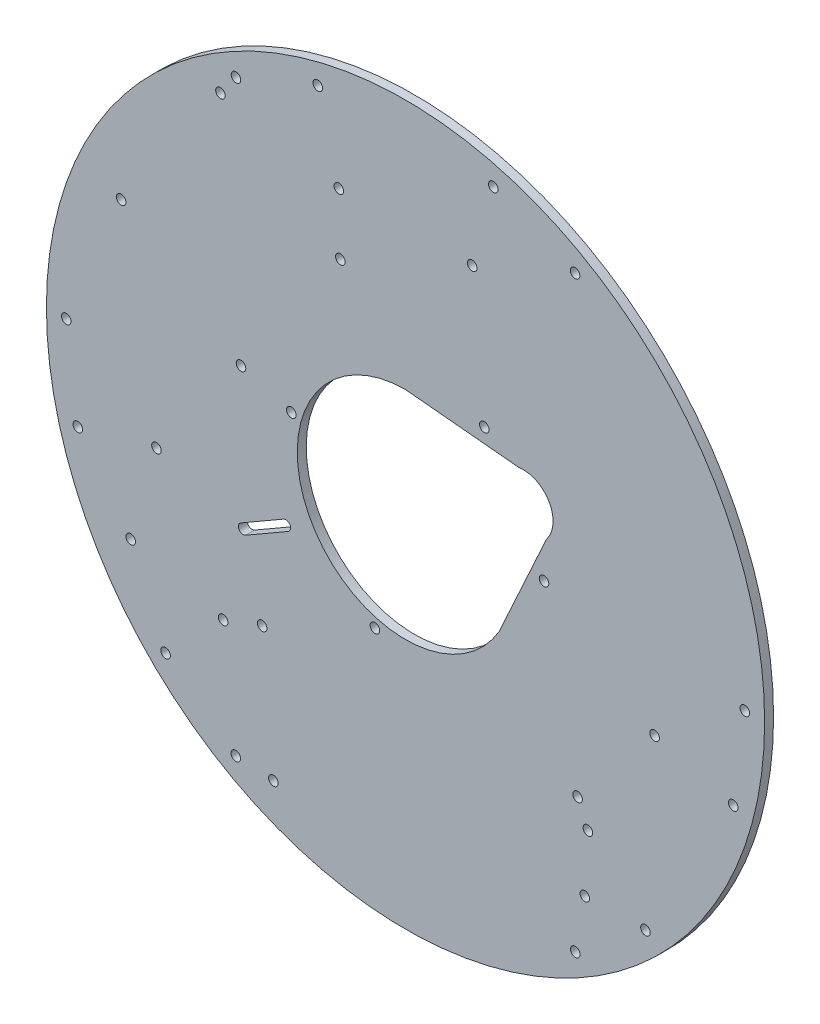
SolidWorks part; units mm, degrees
ref_plane "Front Plane" through (0, 0, 0) normal (0, 0, 1) x (1, 0, 0)
ref_plane "Top Plane" through (0, 0, 0) normal (0, 1, 0) x (1, 0, 0)
ref_plane "Right Plane" through (0, 0, 0) normal (1, 0, 0) x (0, 0, -1)
sketch "Sketch1" plane through (0, 0, 0) normal (0, 0, 1) x (1, 0, 0)
  line L0 (-65.1101, 48.691) -> (-135.9392, -73.9885)
  line L1 (-135.9392, -73.9885) -> (-113.0524, -113.6295)
  line L2 (-113.0524, -113.6295) -> (28.6057, -113.6295)
  line L3 (28.6057, -113.6295) -> (51.4924, -73.9885)
  line L4 (51.4924, -73.9885) -> (-19.3366, 48.691)
  line L5 (-19.3366, 48.691) -> (-65.1101, 48.691)
  line L9 (-42.2234, -10.309) -> (-2.8192, -14.059)
  line L10 (-10.83, -64.684) -> (5.6245, -28.684)
  circle A0 centre (-15.8503, -7.9885) radius 1.6
  circle A1 centre (4.1497, -42.6295) radius 1.6
  circle A2 centre (-80.4721, -36.0603) radius 1.6
  circle A3 centre (-52.4721, -84.5577) radius 1.6
  arc A4 (-42.2234, -10.309) -> (-10.83, -64.684) centre (-42.2234, -46.559) ccw
  arc A5 (5.6245, -28.684) -> (-2.8192, -14.059) centre (-2.8192, -23.809) ccw
extrude "Boss-Extrude1" add sketch "Sketch1" along normal blind 3
sketch "Sketch2" plane through (0, 0, 3) normal (0, 0, 1) x (1, 0, 0)
  circle A0 centre (-2.8192, -23.809) radius 10
extrude "Cut-Extrude1" cut sketch "Sketch2" against normal through all
sketch "Sketch3" plane through (0, 0, 3) normal (0, 0, 1) x (1, 0, 0)
  line L0 (-65.1101, 48.691) -> (-65.1101, 71.4883)
  circle A0 centre (-42.2234, -46.559) radius 120.2454
extrude "Boss-Extrude2" add sketch "Sketch3" against normal blind 3
sketch "Sketch4" plane through (0, 0, 0) normal (0, 0, -1) x (-1, 0, 0)
  line L0 (-5.841, -18.809) -> (73.6168, -64.684)
  line L1 (73.6168, -64.684) -> (146.359, -106.6817)
  line L2 (42.2234, -46.559) -> (31.7433, -166.3468)
  line L3 (42.2234, -46.559) -> (140.7227, 22.411)
  line L4 (35.8225, -119.7215) -> (93.082, -124.731)
  line L9 (93.082, -124.731) -> (95.2909, -99.4825)
  line L10 (95.2909, -99.4825) -> (-19.2715, -89.4596)
  line L11 (-19.2715, -89.4596) -> (-23.6894, -139.9567)
  line L12 (-23.6894, -139.9567) -> (90.873, -149.9796)
  line L13 (90.873, -149.9796) -> (93.082, -124.731)
  line L14 (-23.6894, -139.9567) -> (-18.9575, -140.3707)
  line L15 (-18.9575, -140.3707) -> (-17.8026, -127.1711)
  line L16 (90.873, -149.9796) -> (86.1411, -149.5656)
  line L17 (86.1411, -149.5656) -> (86.4679, -145.8299)
  line L18 (106.598, -1.4834) -> (129.5343, 14.5768)
  line L19 (129.5343, 14.5768) -> (153.7938, -20.0694)
  line L20 (153.7938, -20.0694) -> (107.9213, -52.1897)
  line L22 (59.1673, 17.4382) -> (105.0398, 49.5585)
  line L23 (105.0398, 49.5585) -> (129.5343, 14.5768)
  line L24 (105.0398, 49.5585) -> (107.0473, 46.6914)
  line L25 (107.0473, 46.6914) -> (104.1803, 44.6839)
  line L26 (59.1673, 17.4382) -> (61.1748, 14.5712)
  line L27 (61.1748, 14.5712) -> (107.9213, -52.1897)
  line L28 (61.1748, 14.5712) -> (64.0419, 16.5787)
  line L29 (104.1803, 44.6839) -> (137.4477, -2.8269)
  line L30 (137.4477, -2.8269) -> (97.3093, -30.9321)
  line L31 (64.0419, 16.5787) -> (97.3093, -30.9321)
  line L33 (-14.5395, -89.8736) -> (-15.3893, -99.5865)
  arc A1 (4.2952, -13.9185) -> (-5.0082, -30.0325) centre (2.8192, -23.809) ccw construction
  arc A2 (10.83, -64.684) -> (42.2234, -10.309) centre (42.2234, -46.559) ccw construction
  circle A3 centre (42.2234, -46.559) radius 120.2454 construction
  circle A7 centre (104.1803, 44.6839) radius 1.6
  circle A8 centre (64.0419, 16.5787) radius 1.6
  circle A9 centre (137.4477, -2.8269) radius 1.6
  circle A10 centre (97.3093, -30.9321) radius 1.6
  circle A11 centre (-17.8026, -127.1711) radius 1.6
  circle A12 centre (-15.3893, -99.5865) radius 1.6
  circle A13 centre (86.4679, -145.8299) radius 1.6
  circle A14 centre (90.2322, -102.8042) radius 1.6
  point P2 (35.8225, -119.7215)
  point P15 (35.8225, -119.7215)
  point P33 (106.598, -1.4834)
  dimension "D3" = 90
  dimension "D1" = 115
  dimension "D2" = 115
  dimension "D4" = 90
  dimension "D5" = 90
extrude "Cut-Extrude2" cut sketch "Sketch4" against normal blind 10
sketch "Sketch5" plane through (0, 0, 0) normal (0, 0, -1) x (-1, 0, 0)
  line L0 (42.2234, -46.559) -> (73.6168, -64.684)
  line L1 (73.6168, -64.684) -> (82.2771, -69.684)
  line L2 (82.2771, -69.684) -> (134.2386, -99.684)
  line L3 (82.2771, -69.684) -> (83.0771, -68.2983)
  line L4 (96.5859, -77.9452) -> (97.3859, -76.5595)
  line L5 (96.5859, -77.9452) -> (95.7859, -79.3308)
  line L6 (83.0771, -68.2983) -> (97.3859, -76.5595)
  line L7 (81.4979, -71.0814) -> (82.2771, -69.684)
  line L8 (81.4979, -71.0814) -> (95.7859, -79.3308)
  arc A0 (10.83, -64.684) -> (42.2234, -10.309) centre (42.2234, -46.559) ccw construction
  circle A1 centre (82.2771, -69.684) radius 1.6
  circle A2 centre (134.2386, -99.684) radius 1.6
  circle A3 centre (96.5859, -77.9452) radius 1.6
  dimension "D1" = 90
  dimension "D2" = 90
extrude "Cut-Extrude4" cut sketch "Sketch5" against normal through all
sketch "Sketch6" plane through (0, 0, 0) normal (0, 0, -1) x (-1, 0, 0)
  line L0 (42.2234, -46.559) -> (140.6109, -103.363)
  line L1 (42.2234, -46.559) -> (151.9552, -75.9821)
  line L2 (42.2234, -46.559) -> (155.8315, -46.5986)
  line L3 (151.9552, -75.9821) -> (125.6157, -68.9195)
  line L4 (42.2234, -46.559) -> (42.2234, -160.1671)
  line L5 (42.2234, -46.559) -> (140.6109, 10.2451)
  circle A0 centre (42.2234, -46.559) radius 113.6081
  circle A1 centre (155.8315, -46.5986) radius 1.6
  circle A2 centre (151.9552, -75.9821) radius 1.6
  circle A3 centre (125.6157, -68.9195) radius 1.6
  circle A4 centre (103.2843, -107.5986) radius 1.6
  circle A5 centre (122.5705, -126.878) radius 1.6
  circle A6 centre (99.0618, -144.9267) radius 1.6
  circle A7 centre (98.9931, 51.8483) radius 1.6
  circle A8 centre (71.6082, 63.1831) radius 1.6
  circle A9 centre (64.5548, 36.8411) radius 1.6
  circle A10 centre (12.8386, 63.1831) radius 1.6
  circle A11 centre (-14.5463, 51.8483) radius 1.6
  circle A12 centre (19.892, 36.8411) radius 1.6
  circle A13 centre (-41.1689, -68.9195) radius 1.6
  circle A14 centre (-67.5085, -75.9821) radius 1.6
  circle A15 centre (-71.3847, -46.5986) radius 1.6
  circle A16 centre (-38.1237, -126.878) radius 1.6
  circle A17 centre (-14.615, -144.9267) radius 1.6
  circle A18 centre (-18.8375, -107.5986) radius 1.6
  dimension "D1" = 14.99
  dimension "D3" = 60
  dimension "D2" = 14.99
  dimension "D4" = 60
extrude "Cut-Extrude5" cut sketch "Sketch6" against normal through all contours A0 A11 | A0 A11 | A0 A10 | A0 A10 | A12 | A9 | A7 A0 | A7 A0 | L2 A1 A0 | A0 A1 L2 | A0 A1 | L1 A3 | L1 A3 | A0 A2 L3 | L3 A2 A0 | A0 A2 | A4 | A5 A0 | A5 A0 | A6 A0 | A6 A0 | A15 A0 | A15 A0 | A14 A0 | A14 A0 | A13 | A18 | A0 A16 | A0 A16 | A0 A17 | A0 A17 | A8
